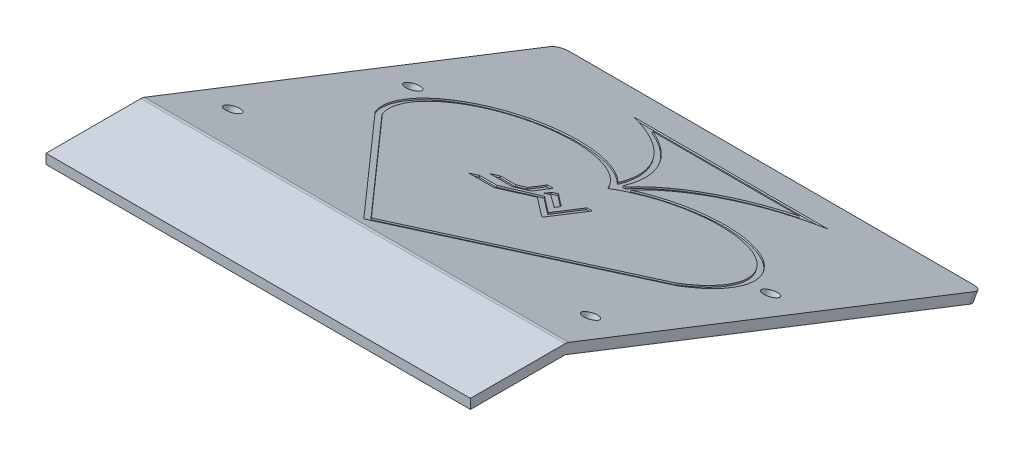
SolidWorks part; units mm, degrees
ref_plane "Plano frontal" through (0, 0, 0) normal (0, 0, 1) x (1, 0, 0)
ref_plane "Plano superior" through (0, 0, 0) normal (0, 1, 0) x (1, 0, 0)
ref_plane "Plano direito" through (0, 0, 0) normal (1, 0, 0) x (0, 0, -1)
sketch "Esboço1" plane through (0, 0, 0) normal (1, 0, 0) x (0, 0, -1)
  line L0 (0, 2) -> (19.99, 2)
  line L1 (19.61, 0) -> (0, 0)
  line L2 (19.99, 2) -> (106.12, -31.7453)
  line L3 (105.11, -33.4985) -> (19.61, 0)
  line L4 (0, 2) -> (0, 0)
  line L5 (106.12, -31.7453) -> (105.11, -33.4985)
  dimension "D1" = 19.61
  dimension "D2" = 19.99
  dimension "D3" = 105.11
  dimension "D4" = 106.12
  dimension "D5" = 2
  dimension "D6" = 31.7453
extrude "Ressalto-extrusão1" add sketch "Esboço1" along normal blind 87.78
sketch "Esboço2" plane through (0, 8.5236, -3.3395) normal (0, 0.9311, -0.3648) x (1, 0, 0)
  circle A0 centre (80.8, 30.5876) radius 1.55 construction
  circle A1 centre (80.8, 30.5876) radius 1.55
  circle A2 centre (6.8, 30.5876) radius 1.55 construction
  circle A3 centre (6.8, 30.5876) radius 1.55
  circle A4 centre (80.8, 70.5876) radius 1.55 construction
  circle A5 centre (80.8, 70.5876) radius 1.55
  circle A6 centre (6.8, 70.5876) radius 1.55 construction
  circle A7 centre (6.8, 70.5876) radius 1.55
extrude "Corte-extrusão1" cut sketch "Esboço2" against normal up to surface (2.0008 mm away) up to face at (43.89, -16.7493, -62.36)
fillet "Filete1" radius 2 2 edges at (0, -32.6219, -105.615) (87.78, -32.6219, -105.615)
fillet "Filete2" radius 2 1 edges at (43.89, 2, -19.99)
sketch "Esboço4" plane through (0, 8.5236, -3.3395) normal (0, 0.9311, -0.3648) x (1, 0, 0)
  line L0 (43.89, 21.5519) -> (43.89, 91.5519) construction
  line L1 (99.9585, 56.5537) -> (-12.1785, 56.55) construction
  line L2 (43.89, 21.5519) -> (13.5797, 56.5509)
  line L3 (43.89, 21.5519) -> (74.2015, 56.5529)
  line L4 (59.0454, 100.3019) -> (28.7346, 100.3019)
  line L5 (87.78, -0.7296) -> (0, -0.7296) construction
  line L6 (87.78, -0.7296) -> (0, -0.7296) construction
  line L7 (43.89, -0.7296) -> (43.89, 4.4324) construction
  line L8 (0, 108.3651) -> (0, 18.2607) construction
  line L9 (0, 108.3651) -> (0, 18.2607) construction
  circle A0 centre (43.89, 56.5519) radius 17.5 construction
  circle A1 centre (43.89, 39.0519) radius 17.5 construction
  circle A2 centre (28.7346, 47.8019) radius 17.5 construction
  circle A3 centre (59.0454, 47.8019) radius 17.5 construction
  arc A4 (43.89, 74.0519) -> (13.5797, 56.5509) centre (28.7346, 65.3019) ccw
  arc A5 (74.2015, 56.5529) -> (43.89, 74.0519) centre (59.0454, 65.3019) ccw
  circle A6 centre (28.7346, 30.3019) radius 17.5 construction
  circle A7 centre (59.0454, 30.3019) radius 17.5 construction
  circle A8 centre (43.89, 74.0519) radius 17.5 construction
  circle A9 centre (28.7346, 82.8019) radius 17.5 construction
  circle A10 centre (59.0454, 82.8019) radius 17.5 construction
  arc A11 (59.0454, 100.3019) -> (43.89, 74.0519) centre (74.2009, 74.0519) ccw
  arc A12 (43.89, 74.0519) -> (28.7346, 100.3019) centre (13.5791, 74.0519) ccw
  arc A13 (43.89, 74.0519) -> (43.89, 56.5519) centre (28.7346, 65.3019) cw construction
  arc A14 (28.7346, 47.8019) -> (43.89, 56.5519) centre (28.7346, 65.3019) ccw construction
  arc A15 (43.89, 56.5519) -> (28.7346, 47.8019) centre (28.7346, 65.3019) cw construction
  arc A16 (28.7346, 47.8019) -> (24.7873, 48.2528) centre (28.7346, 65.3019) cw construction
  arc A17 (17.9085, 51.5525) -> (24.7873, 48.2528) centre (28.7346, 65.3019) ccw construction
  arc A18 (24.7873, 48.2528) -> (17.9085, 51.5525) centre (28.7346, 65.3019) cw construction
  arc A19 (17.9085, 51.5525) -> (13.5797, 56.5509) centre (28.7346, 65.3019) cw construction
  arc A20 (13.5797, 56.5509) -> (17.9085, 51.5525) centre (28.7346, 65.3019) ccw construction
  arc A21 (43.89, 56.5519) -> (43.89, 74.0519) centre (28.7346, 65.3019) ccw construction
  arc A22 (43.89, 74.0519) -> (43.89, 56.5519) centre (59.0454, 65.3019) ccw construction
  arc A23 (43.89, 56.5519) -> (59.0454, 47.8019) centre (59.0454, 65.3019) ccw construction
  arc A24 (59.0454, 47.8019) -> (69.87, 51.5512) centre (59.0454, 65.3019) ccw construction
  arc A25 (69.87, 51.5512) -> (74.2015, 56.5529) centre (59.0454, 65.3019) ccw construction
  point P4 (43.89, 56.5519)
  point P28 (13.5797, 56.5509)
  point P34 (43.89, 56.5519)
  point P35 (74.2015, 56.5529)
  dimension "D2" = 35
  dimension "D1" = 70
  dimension "D3" = 57.28
sketch "Esboço5" plane through (0, 8.5236, -3.3395) normal (0, 0.9311, -0.3648) x (1, 0, 0)
  line L0 (59.0454, 100.3019) -> (28.7346, 100.3019) construction
  line L1 (43.89, 21.5519) -> (74.2015, 56.5529) construction
  line L2 (43.89, 21.5519) -> (13.5797, 56.5509) construction
  line L3 (59.0454, 100.3019) -> (28.7346, 100.3019)
  line L4 (43.89, 21.5519) -> (74.2015, 56.5529)
  line L5 (43.89, 21.5519) -> (13.5797, 56.5509)
  line L6 (43.89, 19.8716) -> (12.6806, 55.9088)
  line L7 (43.89, 19.8716) -> (75.1006, 55.9109)
  line L8 (63.9416, 101.4019) -> (23.8384, 101.4019)
  line L9 (59.0454, 101.4019) -> (28.7346, 101.4019) construction
  line L10 (43.6636, 77.75) -> (44.1164, 77.75)
  arc A0 (43.89, 74.0519) -> (28.7346, 100.3019) centre (13.5791, 74.0519) ccw construction
  arc A1 (59.0454, 100.3019) -> (43.89, 74.0519) centre (74.2009, 74.0519) ccw construction
  arc A2 (74.2015, 56.5529) -> (43.89, 74.0519) centre (59.0454, 65.3019) ccw construction
  arc A3 (43.89, 74.0519) -> (13.5797, 56.5509) centre (28.7346, 65.3019) ccw construction
  arc A4 (43.6636, 77.75) -> (28.7346, 100.3019) centre (13.5791, 74.0519) ccw
  arc A5 (59.0454, 100.3019) -> (44.1164, 77.75) centre (74.2009, 74.0519) ccw
  arc A6 (74.2015, 56.5529) -> (43.89, 74.0519) centre (59.0454, 65.3019) ccw
  arc A7 (43.89, 74.0519) -> (13.5797, 56.5509) centre (28.7346, 65.3019) ccw
  arc A9 (75.1006, 55.9109) -> (45.225, 77.75) centre (59.0454, 65.3019) ccw
  arc A10 (42.555, 77.75) -> (23.8384, 101.4019) centre (13.5791, 74.0519) ccw
  arc A11 (63.9416, 101.4019) -> (45.225, 77.75) centre (74.2009, 74.0519) ccw
  arc A12 (59.5954, 99.3492) -> (44.99, 74.0519) centre (74.2009, 74.0519) ccw construction
  arc A13 (42.79, 74.0519) -> (28.1846, 99.3492) centre (13.5791, 74.0519) ccw construction
  arc A14 (43.89, 74.0519) -> (28.7346, 100.3019) centre (13.5791, 74.0519) ccw construction
  arc A15 (59.0454, 100.3019) -> (43.89, 74.0519) centre (74.2009, 74.0519) ccw construction
  arc A17 (75.1006, 55.9109) -> (43.89, 76.0848) centre (59.0454, 65.3019) ccw construction
  arc A18 (42.555, 77.75) -> (12.6806, 55.9088) centre (28.7346, 65.3019) ccw
  arc A19 (43.89, 76.0848) -> (12.6806, 55.9088) centre (28.7346, 65.3019) ccw construction
  dimension "D2" = 60.6218
  dimension "D3" = 1.1
  dimension "D4" = 1.1
  dimension "D1" = 1.1
  dimension "D5" = 1.1
extrude "Corte-extrusão2" cut sketch "Esboço5" against normal blind 0.3 contours A10 A18 L6 L7 A9 A11 L8 L3 A5 L10 A4 A7 A6 L4 L5
sketch "Logo_MF" plane through (0, 8.5236, -3.3395) normal (0, 0.9311, -0.3648) x (1, 0, 0)
  line L0 (49.9626, 64.155) -> (48.829, 64.155)
  line L1 (48.829, 64.155) -> (48.829, 55.5351)
  line L2 (48.829, 55.5351) -> (43.89, 60.0216)
  line L3 (43.89, 60.0216) -> (38.9069, 54.7788)
  line L4 (38.9069, 54.7788) -> (35.3881, 54.7788)
  line L5 (35.3881, 54.7788) -> (34.2601, 53.537)
  line L6 (34.2601, 53.537) -> (39.4506, 53.537)
  line L7 (39.4506, 53.537) -> (43.8882, 58.4222)
  line L8 (43.8882, 58.4222) -> (49.9626, 52.9043)
  line L9 (49.9626, 52.9043) -> (49.9626, 64.155)
  line L10 (47.5203, 58.2743) -> (47.5203, 59.8448)
  line L11 (47.5203, 59.8448) -> (43.6399, 63.3698)
  line L12 (43.6399, 63.3698) -> (42.959, 62.6202)
  line L13 (42.959, 62.6202) -> (42.959, 60.9001)
  line L14 (42.959, 60.9001) -> (43.641, 61.6509)
  line L15 (43.641, 61.6509) -> (47.5203, 58.2743)
  line L16 (41.859, 64.155) -> (41.859, 59.313)
  line L17 (41.859, 59.313) -> (39.859, 57.2088)
  line L18 (39.859, 57.2088) -> (35.1755, 57.2088)
  line L19 (35.1755, 57.2088) -> (36.3279, 58.4212)
  line L20 (36.3279, 58.4212) -> (39.4501, 58.4212)
  line L21 (39.4501, 58.4212) -> (40.644, 59.6773)
  line L22 (40.644, 59.6773) -> (40.644, 64.155)
  line L23 (40.644, 64.155) -> (41.859, 64.155)
  line L24 (43.89, 74.0519) -> (43.89, 21.5519) construction
  line L25 (0, 108.3651) -> (0, 18.2607) construction
  line L26 (0, 18.2607) -> (87.78, 18.2607) construction
  dimension "D1" = 2.43
  dimension "D2" = 6.97
  dimension "D3" = 1.1
  dimension "D4" = 34.2601
  dimension "D5" = 35.1755
  dimension "D6" = 35.3881
  dimension "D7" = 36.3279
  dimension "D8" = 38.9069
  dimension "D9" = 39.4501
  dimension "D10" = 39.4506
  dimension "D11" = 39.859
  dimension "D12" = 40.644
  dimension "D13" = 41.859
  dimension "D14" = 47.5203
  dimension "D15" = 43.6399
  dimension "D16" = 43.641
  dimension "D17" = 43.8882
  dimension "D18" = 43.89
  dimension "D19" = 49.9626
  dimension "D20" = 34.6436
  dimension "D21" = 87.78
  dimension "D22" = 35.2763
  dimension "D23" = 37.2745
  dimension "D24" = 41.5842
  dimension "D25" = 40.0137
  dimension "D26" = 42.6394
  dimension "D27" = 45.8944
  dimension "D37" = 90.1044
extrude "Corte-extrusão3" cut sketch "Logo_MF" against normal blind 0.3
